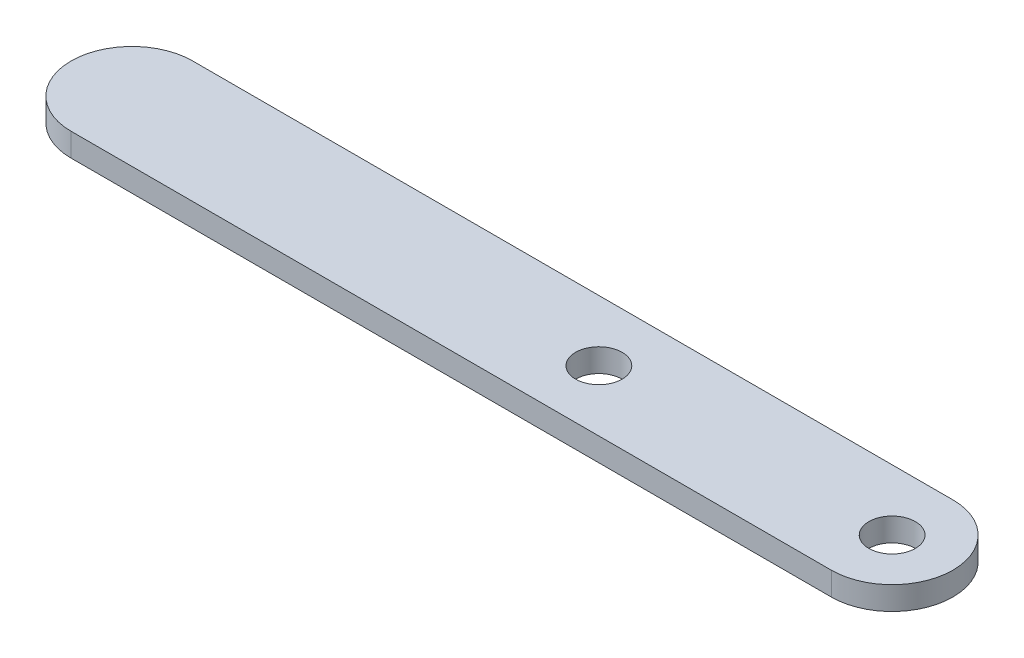
SolidWorks part; units mm, degrees
material "6061-T6 (SS)"
ref_plane "Front Plane" through (0, 0, 0) normal (0, 0, 1) x (1, 0, 0)
ref_plane "Top Plane" through (0, 0, 0) normal (0, 1, 0) x (1, 0, 0)
ref_plane "Right Plane" through (0, 0, 0) normal (1, 0, 0) x (0, 0, -1)
sketch "Sketch1" plane through (0, 0, 0) normal (0, 1, 0) x (1, 0, 0)
  line L0 (-28, 0) -> (28, 0) construction
  line L1 (28, 4.15) -> (8, 4.15)
  line L2 (8, 4.15) -> (-23.85, 4.15)
  line L3 (-23.85, -4.15) -> (8, -4.15)
  line L4 (8, -4.15) -> (28, -4.15)
  circle A0 centre (8, 0) radius 1.5875
  circle A1 centre (28, 0) radius 1.5875
  arc A3 (-23.85, 4.15) -> (-23.85, -4.15) centre (-23.85, 0) ccw
  arc A4 (28, -4.15) -> (28, 4.15) centre (28, 0) ccw
  point P2 (0, 0)
  point P5 (8, 0)
  dimension "D3" = 3.175
  dimension "D1" = 56
  dimension "D2" = 20
  dimension "D4" = 8.3
extrude "Boss-Extrude1" add sketch "Sketch1" along normal mid plane 1.5875
